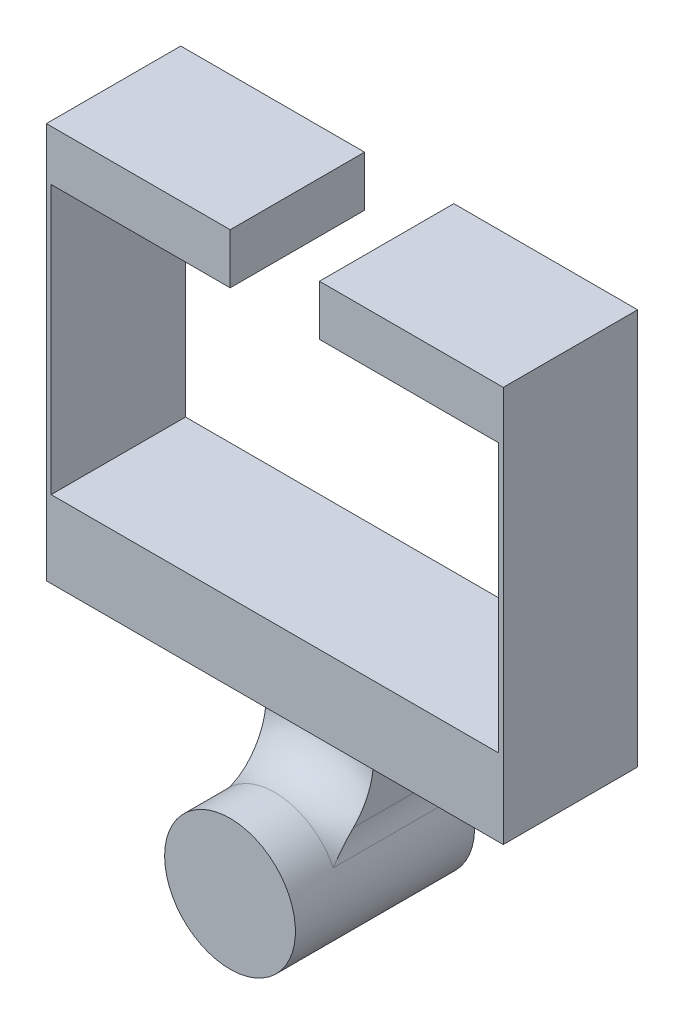
SolidWorks part; units mm, degrees
material "Ti-6Al-4VSolution treated and aged (SS)"
ref_plane "Front Plane" through (0, 0, 0) normal (0, 0, 1) x (1, 0, 0)
ref_plane "Top Plane" through (0, 0, 0) normal (0, 1, 0) x (1, 0, 0)
ref_plane "Right Plane" through (0, 0, 0) normal (1, 0, 0) x (0, 0, -1)
sketch "Sketch4" plane through (0, 0, 0) normal (0, 0, 1) x (1, 0, 0)
  line L0 (-75.0023, 84.8731) -> (-10.2323, 84.8731)
  line L1 (-10.2323, 84.8731) -> (-10.2323, 28.7391)
  line L2 (-10.2323, 28.7391) -> (-75.0023, 28.7391)
  line L3 (-75.0023, 28.7391) -> (-75.0023, 84.8731)
  dimension "D1" = 64.77
  dimension "D2" = 56.134
extrude "Boss-Extrude1" add sketch "Sketch4" along normal blind 19.05
sketch "Sketch5" plane through (0, 0, 19.05) normal (0, 0, 1) x (1, 0, 0)
  line L0 (-42.6173, 28.7391) -> (-42.6173, 88.7394) construction
  line L1 (-75.0023, 28.7391) -> (-10.2323, 28.7391) construction
  line L2 (-74.3216, 39.6611) -> (-10.913, 39.6611)
  line L3 (-10.913, 39.6611) -> (-10.913, 77.7357)
  line L4 (-10.913, 77.7357) -> (-36.2927, 77.7357)
  line L5 (-36.2927, 77.7357) -> (-36.2927, 84.8731)
  line L6 (-10.2323, 84.8731) -> (-75.0023, 84.8731) construction
  line L8 (-48.9419, 77.7357) -> (-48.9419, 84.8731)
  line L9 (-74.3216, 39.6611) -> (-74.3216, 77.7357)
  line L10 (-74.3216, 77.7357) -> (-48.9419, 77.7357)
  line L11 (-48.9419, 84.8731) -> (-36.2927, 84.8731)
  point P12 (-42.6173, 39.6611)
  dimension "D1" = 12.6492
  dimension "D2" = 10.922
  dimension "D3" = 38.0746
  dimension "D4" = 7.1374
  dimension "D5" = 25.3797
  dimension "D6" = 63.4086
extrude "Cut-Extrude1" cut sketch "Sketch5" against normal through all
sketch "Sketch6" plane through (0, 28.7391, 0) normal (0, -1, 0) x (1, 0, 0)
  line L0 (-42.6173, 0) -> (-42.6173, 31.0162) construction
  line L1 (-75.0023, 0) -> (-10.2323, 0) construction
  line L2 (-42.6173, 0) -> (-34.9973, 0)
  line L3 (-34.9973, 0) -> (-34.9973, 12.7)
  line L4 (-42.6173, 0) -> (-50.2373, 0)
  line L5 (-50.2373, 0) -> (-50.2373, 12.7)
  line L6 (-50.2373, 12.7) -> (-34.9973, 12.7)
  point P4 (-38.8073, 0)
  dimension "D1" = 15.24
  dimension "D2" = 12.7
extrude "Boss-Extrude2" add sketch "Sketch6" along normal blind 19.05
sketch "Sketch7" plane through (0, 0, 0) normal (0, 0, -1) x (-1, 0, 0)
  line L0 (50.2373, 9.6891) -> (34.9973, 9.6891) construction
  circle A0 centre (42.6173, 9.6891) radius 9.271
  dimension "D1" = 18.542
extrude "Boss-Extrude3" add sketch "Sketch7" against normal blind 25.4
fillet "Fillet1" radius 6.35 3 edges at (-50.2373, 14.97, 6.35) (-42.6173, 18.9601, 12.7) (-34.9973, 14.97, 6.35)
equation "\"Ad\"= .726in"
equation "\"C\"= .433in"
equation "\"E\"= .274in"
equation "\"SigmaAllow\"= 32000"
equation "\"LoadB\"= 1200"
equation "\"LoadD\"= 600"
equation "\"WidthB\"= .25in"
equation "\"B\"= \"LoadB\" / ( \"WidthB\" * \"SigmaAllow\" ) * 1in"
equation "\"D\"= \"LoadD\" / ( \"WidthD\" * \"SigmaAllow\" ) * 1in'For min t geometric required more"
equation "\"AT\"= .498in"
equation "\"BT\"= .9992in"
equation "\"CT\"= 1.499in"
equation "\"WidthD\"= .75in"
